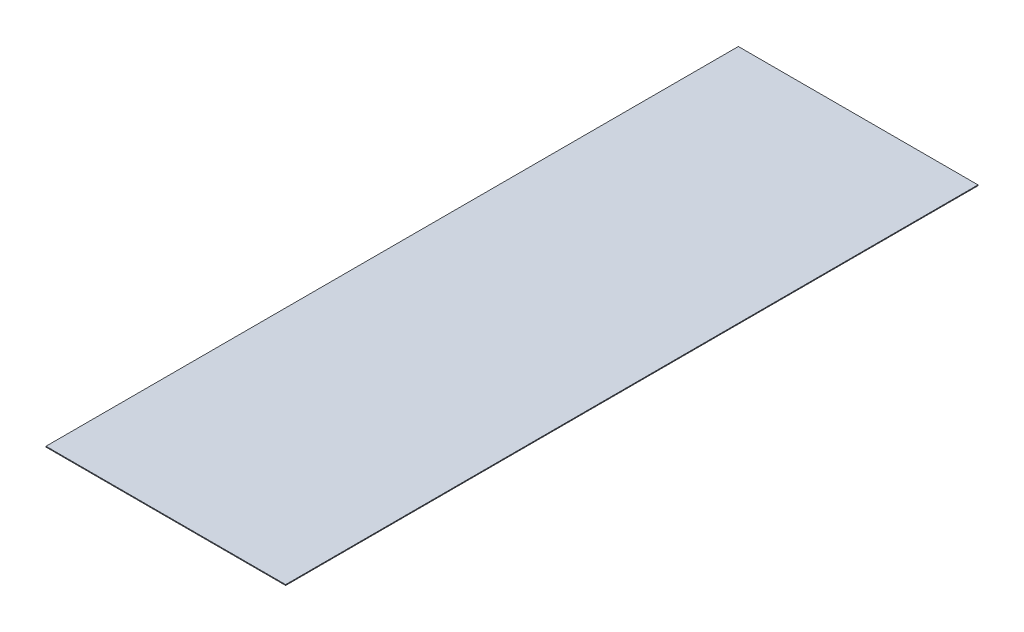
SolidWorks part; units mm, degrees
material "AISI 1018 mild/low carbon Stel"
ref_plane "Front Plane" through (0, 0, 0) normal (0, 0, 1) x (1, 0, 0)
ref_plane "Top Plane" through (0, 0, 0) normal (0, 1, 0) x (1, 0, 0)
ref_plane "Right Plane" through (0, 0, 0) normal (1, 0, 0) x (0, 0, -1)
sketch3d "Suspension Geometry"
  line L0 (0, 0, 150) -> (0, 0, -1405) construction
  line L1 (-213.81, 145.8, 150) -> (213.81, 145.8, 150)
  line L2 (213.81, 145.8, 150) -> (247.07, 302.3, 150)
  line L3 (0, 145.8, 150) -> (0, 0, 150) construction
  line L4 (-247.07, 302.3, 150) -> (247.07, 302.3, 150)
  line L5 (-247.07, 302.3, 150) -> (-213.81, 145.8, 150)
  line L6 (0, 0, -1405) -> (0, 140, -1405) construction
  line L7 (-233.58, 140, -1405) -> (233.58, 140, -1405)
  line L8 (-282.5, 300, -1405) -> (282.5, 300, -1405)
  line L9 (-282.5, 300, -1405) -> (-233.58, 140, -1405)
  line L10 (282.5, 300, -1405) -> (233.58, 140, -1405)
  point P7 (0, 145.8, 150)
  point P12 (0, 140, -1405)
  point P13 (0, 302.3, 150)
  point P17 (0, 300, -1405)
  dimension "D1" = 150
  dimension "D2" = 494.14
  dimension "D3" = 427.62
  dimension "D4" = 145.8
  dimension "D5" = 156.5
  dimension "D6" = 1555
  dimension "D7" = 140
  dimension "D8" = 467.16
  dimension "D9" = 565
  dimension "D10" = 160
sketch3d "Suspension Box"
  line L0 (-282.5, 300, -1405) -> (-282.5, 300, -1145)
  line L1 (-233.58, 140, -1405) -> (-233.58, 140, -1145)
  line L2 (282.5, 300, -1405) -> (282.5, 300, -1145)
  line L3 (233.58, 140, -1405) -> (233.58, 140, -1145)
  line L4 (-282.5, 300, -1145) -> (282.5, 300, -1145) construction
  line L5 (-282.5, 300, -1145) -> (-233.58, 140, -1145) construction
  line L6 (-233.58, 140, -1405) -> (233.58, 140, -1405) construction
  line L7 (282.5, 300, -1145) -> (233.58, 140, -1145) construction
  line L16 (-213.81, 145.8, 0) -> (-213.81, 145.8, 300)
  line L19 (-247.07, 302.3, 0) -> (-247.07, 302.3, 300)
  line L22 (247.07, 302.3, 0) -> (247.07, 302.3, 300)
  line L26 (213.81, 145.8, 0) -> (213.81, 145.8, 300)
  line L28 (-247.07, 302.3, 0) -> (-213.81, 145.8, 0)
  line L29 (247.07, 302.3, 0) -> (213.81, 145.8, 0)
  line L30 (247.07, 302.3, 300) -> (213.81, 145.8, 300)
  line L31 (-247.07, 302.3, 300) -> (-213.81, 145.8, 300)
  point P6 (213.81, 145.8, 150)
  point P8 (-233.58, 140, -1405)
  point P12 (247.07, 302.3, 150)
  point P15 (-282.5, 300, -1405)
  point P16 (-247.07, 302.3, 150)
  point P18 (-213.81, 145.8, 150)
  point P19 (282.5, 300, -1405)
  point P24 (233.58, 140, -1405)
  point P32 (-213.81, 145.8, 150)
  point P35 (-247.07, 302.3, 150)
  point P38 (213.81, 145.8, 150)
  point P40 (247.07, 302.3, 150)
  dimension "D1" = 260
  dimension "D2" = 300
sketch "Percy" plane through (0, 0, 0) normal (1, 0, 0) x (0, 0, -1)
  line L0 (670, 853.9654) -> (670, 573.9654)
  line L1 (670, 573.9654) -> (323.5177, 227.4831)
  line L2 (770, 1191.5162) -> (770, 65) construction
  line L3 (670, 573.9654) -> (670, 368.4293) construction
  line L4 (770, 65) -> (0, 145.8) construction
  line L5 (-52.8264, 166.4257) -> (360.5084, 123.0524) construction
  line L6 (870, 632.544) -> (360.5084, 123.0524)
  line L7 (870, 1120.8087) -> (870, 632.544)
  line L8 (0, 635) -> (770, 1191.5162) construction
  line L9 (323.5177, 227.4831) -> (-582.4403, 355.8)
  line L10 (-150, 65) -> (1405, 65) construction
  line L11 (-150, 0) -> (1405, 0) construction
  line L12 (-0.6994, 554.2948) -> (769.3006, 1110.8109) construction
  circle A0 centre (670, 853.9654) radius 150
  circle A1 centre (670, 573.9654) radius 100
  circle A2 centre (323.5177, 227.4831) radius 100
  point P13 (-875, 145.8)
  point P24 (0, 635)
  point P32 (770, 330)
  dimension "D1" = 200
  dimension "D2" = 300
  dimension "D3" = 280
  dimension "D4" = 490
  dimension "D5" = 45
  dimension "D6" = 15
  dimension "D7" = 770
  dimension "D8" = 200
  dimension "D9" = 875
  dimension "D10" = 915
  dimension "D11" = 210
  dimension "D12" = 65
  dimension "D13" = 570
  dimension "D14" = 65
  dimension "D15" = 265
ref_plane "FH Plane" through (0, 0, 0) normal (0, 0, -1) x (-1, 0, 0)
ref_plane "MH Plane" through (0, 0, -770) normal (0, 0, -1) x (-1, 0, 0)
ref_plane "RBH Plane" through (0, 0, -1405) normal (0, 0, -1) x (-1, 0, 0)
sketch "Sketch2" plane through (0, 0, -770) normal (0, 0, -1) x (-1, 0, 0)
  line L0 (340, 330) -> (-340, 330)
  point P4 (0, 330)
  dimension "D1" = 680
sketch3d "Roll Hoop"
  line L0 (-290, 65, -770) -> (290, 65, -770)
  line L1 (-213.81, 145.8, 0) -> (213.81, 145.8, 0)
  line L2 (-213.81, 145.8, 0) -> (-247.07, 302.3, 0)
  line L4 (-290, 65, -770) -> (-338.2032, 306.5, -770)
  line L6 (290, 65, -770) -> (338.2032, 306.5, -770)
  line L8 (213.81, 145.8, 0) -> (247.07, 302.3, 0)
  line L9 (-249.2546, 535, 0) -> (-249.2546, 323.0881, 0)
  line L10 (249.2546, 535, 0) -> (249.2546, 323.0881, 0)
  line L11 (336.1267, 353.2481, -770) -> (115.1326, 1105.3463, -770)
  line L12 (-115.1326, 1105.3463, -770) -> (-336.1267, 353.2481, -770)
  line L13 (-149.2546, 635, 0) -> (149.2546, 635, 0)
  arc A2 (-338.2032, 306.5, -770) -> (-336.1267, 353.2481, -770) centre (-242.2267, 325.6569, -770) ccw
  arc A5 (249.2546, 535, 0) -> (149.2546, 635, 0) centre (149.2546, 535, 0) ccw
  arc A6 (-249.2546, 535, 0) -> (-149.2546, 635, 0) centre (-149.2546, 535, 0) ccw
  arc A7 (247.07, 302.3, 0) -> (249.2546, 323.0881, 0) centre (149.2546, 323.0881, 0) ccw
  arc A8 (-247.07, 302.3, 0) -> (-249.2546, 323.0881, 0) centre (-149.2546, 323.0881, 0) ccw
  arc A9 (115.1326, 1105.3463, -770) -> (-115.1326, 1105.3463, -770) centre (0, 1071.5162, -770) ccw
  arc A10 (336.1267, 353.2481, -770) -> (338.2032, 306.5, -770) centre (242.2267, 325.6569, -770) ccw
  point P8 (0, 65, -770)
  point P13 (242.2267, 325.6569, -867.8698)
  point P23 (0, 1071.5162, -650)
  point P24 (-242.2267, 325.6569, -867.8698)
  point P26 (-340, 330, -770)
  point P27 (0, 1191.5162, -770)
  point P30 (0, 145.8, 0)
  point P35 (-340, 330, -770)
  point P39 (249.2546, 635, 0)
  point P40 (149.2546, 535, 100)
  point P46 (-249.2546, 635, 0)
  point P47 (-149.2546, 535, -100)
  point P48 (0, 635, 0)
  point P50 (249.2546, 312.5793, 0)
  point P51 (149.2546, 323.0881, 100)
  point P54 (-149.2546, 323.0881, -100)
  point P56 (242.5, 635, 0)
  point P59 (-242.5, 635, 0)
  dimension "D2" = 120
  dimension "D5" = 100
  dimension "D1" = 580
  dimension "D4" = 241.5
sketch3d "FBH"
  line L0 (-212.5, 145.8, 875) -> (212.5, 145.8, 875)
  line L1 (212.5, 145.8, 875) -> (212.5, 520.8, 875)
  line L2 (212.5, 520.8, 875) -> (-212.5, 520.8, 875)
  line L3 (-212.5, 520.8, 875) -> (-212.5, 145.8, 875)
  line L4 (-212.5, 520.8, 875) -> (212.5, 145.8, 875)
  line L5 (-210.6176, 65, -1405) -> (210.6176, 65, -1405)
  line L6 (208.7935, 444.65, -1405) -> (282.5, 300, -1405)
  line L7 (-282.5, 300, -1405) -> (-210.6176, 65, -1405)
  line L8 (-208.7935, 444.65, -1405) -> (208.7935, 444.65, -1405)
  line L9 (-282.5, 300, -1405) -> (282.5, 300, -1405) construction
  line L10 (0, 444.65, -1405) -> (0, 414.65, -1405) construction
  line L11 (0, 414.65, -1405) -> (224.08, 414.65, -1405) construction
  line L12 (-208.7935, 444.65, -1405) -> (-282.5, 300, -1405)
  line L13 (210.6176, 65, -1405) -> (282.5, 300, -1405)
  line L14 (0, 414.65, -1405) -> (-224.08, 414.65, -1405) construction
  line L18 (282.5, 300, -1405) -> (233.5606, 140.0059, -1405) construction
  line L19 (-282.5, 300, -1405) -> (-233.5606, 140.0059, -1405) construction
  line L20 (0, 65, 150) -> (0, 65, -1405) construction
  point P4 (0, 145.8, 875)
  point P17 (0, 444.65, -1405)
  point P28 (0, 65, -1405)
  dimension "D1" = 425
  dimension "D2" = 375
  dimension "D4" = 144.65
  dimension "D5" = 224.08
  dimension "D6" = 30
sketch3d "Members"
  line L0 (212.5, 520.8, 875) -> (229.2546, 595, 0)
  line L1 (-212.5, 520.8, 875) -> (-229.2546, 595, 0)
  line L2 (247.07, 302.3, 300) -> (212.5, 520.8, 875)
  line L3 (213.81, 145.8, 300) -> (212.5, 145.8, 875)
  line L4 (-213.81, 145.8, 300) -> (-212.5, 145.8, 875)
  line L5 (-212.5, 145.8, 875) -> (-247.07, 302.3, 300)
  line L6 (-247.07, 302.3, 300) -> (-212.5, 520.8, 875)
  line L7 (-149.2546, 635, 0) -> (149.2546, 635, 0) construction
  line L8 (-247.07, 302.3, 300) -> (-226.3682, 582.2173, 150.739)
  line L9 (210.6176, 65, -1405) -> (282.5, 300, -1405) construction
  line L10 (-282.5, 300, -1405) -> (-210.6176, 65, -1405) construction
  line L11 (248.9273, 315.0042, 0) -> (340, 330, -770)
  line L12 (340, 330, -770) -> (282.5, 300, -1145)
  line L14 (-340, 330, -770) -> (-248.9273, 315.0042, 0)
  line L15 (229.2546, 595, 0) -> (290.0297, 321.772, -347.5123)
  line L16 (340, 330, -770) -> (233.58, 140, -1145)
  line L17 (290.0297, 321.772, -347.5123) -> (213.81, 145.8, 0)
  line L18 (-213.81, 145.8, 0) -> (-290, 65, -770)
  line L19 (290, 65, -770) -> (213.81, 145.8, 0)
  line L20 (-226.3682, 582.2173, 150.739) -> (226.3682, 582.2173, 150.739)
  line L21 (290.0297, 321.772, -347.5123) -> (290, 65, -770)
  line L22 (-229.2546, 595, 0) -> (-290.0297, 321.772, -347.5123)
  line L23 (-340, 330, -770) -> (-282.5, 300, -1145)
  line L25 (290, 65, -770) -> (233.58, 140, -1145)
  line L26 (-290.0297, 321.772, -347.5123) -> (-213.81, 145.8, 0)
  line L27 (-290.0297, 321.772, -347.5123) -> (-290, 65, -770)
  line L28 (226.3682, 582.2173, 150.739) -> (248.9273, 315.0042, 0)
  line L29 (-244.5225, 665, -770) -> (244.5225, 665, -770)
  line L30 (290, 65, -770) -> (210.6176, 65, -1145)
  line L31 (247.07, 302.3, 300) -> (226.3682, 582.2173, 150.739)
  line L32 (-290, 65, -770) -> (290, 65, -770) construction
  line L33 (-246.7006, 110.9193, -332.4027) -> (246.7006, 110.9193, -332.4027)
  line L34 (-223.6508, 135.3638, -99.4539) -> (223.6508, 135.3638, -99.4539)
  line L35 (-213.81, 145.8, 0) -> (213.81, 145.8, 0) construction
  line L36 (247.07, 302.3, 300) -> (212.5, 145.8, 875)
  line L37 (210.6176, 65, -1145) -> (210.6176, 65, -1405)
  line L38 (-226.3682, 582.2173, 150.739) -> (-248.9273, 315.0042, 0)
  line L42 (-290, 65, -770) -> (-210.6176, 65, -1145)
  line L43 (133.8883, 1041.5162, -770) -> (282.5, 300, -1405)
  line L47 (-282.5, 300, -1145) -> (-210.6176, 65, -1145)
  line L51 (210.6176, 65, -1145) -> (282.5, 300, -1145)
  line L52 (-133.8883, 1041.5162, -770) -> (-282.5, 300, -1405)
  line L53 (-133.8883, 1041.5162, -770) -> (133.8883, 1041.5162, -770) construction
  line L54 (-115.1326, 1105.3463, -770) -> (-336.1267, 353.2481, -770) construction
  line L55 (-213.81, 145.8, 300) -> (213.81, 145.8, 300)
  line L57 (336.1267, 353.2481, -770) -> (115.1326, 1105.3463, -770) construction
  line L58 (-210.6176, 65, -1405) -> (-210.6176, 65, -1145)
  line L59 (-282.5, 300, -1405) -> (-282.5, 300, -1402.3763)
  line L60 (282.5, 300, -1405) -> (233.58, 140, -1145)
  line L61 (-210.6176, 65, -1145) -> (210.6176, 65, -1145)
  line L62 (233.58, 140, -1405) -> (210.6176, 65, -1145)
  line L63 (-290, 65, -770) -> (-233.58, 140, -1145)
  line L64 (-233.58, 140, -1145) -> (-340, 330, -770)
  line L65 (-233.58, 140, -1405) -> (-210.6176, 65, -1145)
  line L66 (0, 65, 150) -> (0, 65, -1405) construction
  line L67 (-282.5, 300, -1405) -> (-233.58, 140, -1145)
  arc A0 (247.07, 302.3, 0) -> (249.2546, 323.0881, 0) centre (149.2546, 323.0881, 0) ccw construction
  arc A1 (-247.07, 302.3, 0) -> (-249.2546, 323.0881, 0) centre (-149.2546, 323.0881, 0) ccw construction
  arc A4 (249.2546, 535, 0) -> (149.2546, 635, 0) centre (149.2546, 535, 0) ccw construction
  arc A8 (-249.2546, 535, 0) -> (-149.2546, 635, 0) centre (-149.2546, 535, 0) ccw construction
  point P6 (149.2546, 535, 100)
  point P25 (-149.2546, 535, -100)
  point P51 (149.2546, 323.0881, 100)
  point P91 (0, 65, -1145)
  point P93 (-149.2546, 323.0881, -100)
  dimension "D7" = 150
  dimension "D1" = 40
  dimension "D2" = 172.81
  dimension "D8" = 151.28
  dimension "D3" = 600
  dimension "D4" = 350
  dimension "D5" = 440
  dimension "D6" = 100
other "Square tube 25.4X25.4X1.6(1)"
ref_plane "Plane1" [suppressed] through (212.5, 520.8, 875) normal (-1, 0, 0) x (0, 0, 1)
sketch "Sketch1" [suppressed] plane through (212.5, 520.8, 875) normal (-1, 0, 0) x (0, 0, 1)
  line L0 (-11.1, 11.1) -> (11.1, 11.1)
  line L1 (-12.7, 12.7) -> (12.7, 12.7)
  line L2 (-12.7, 12.7) -> (-12.7, -12.7)
  line L3 (-12.7, -12.7) -> (12.7, -12.7)
  line L4 (12.7, 12.7) -> (12.7, -12.7)
  line L5 (-12.7, 12.7) -> (12.7, -12.7) construction
  line L6 (-12.7, -12.7) -> (12.7, 12.7) construction
  line L7 (11.1, 11.1) -> (11.1, -11.1)
  line L8 (-11.1, -11.1) -> (11.1, -11.1)
  line L9 (-11.1, 11.1) -> (-11.1, -11.1)
  point P0 (0, 0)
  point P10 (0, 0)
  dimension "D1" = 25.4
  dimension "D2" = 25.4
  dimension "D3" = 1.6
other "Pipe 25.4X1.6(1)"
ref_plane "Plane2" [suppressed] through (213.81, 145.8, 300) normal (-0.0023, 0, 1) x (1, 0, 0.0023)
sketch "Sketch11" [suppressed] plane through (213.81, 145.8, 300) normal (-0.0023, 0, 1) x (1, 0, 0.0023)
  circle A0 centre (0, 0) radius 12.7
  circle A1 centre (0, 0) radius 11.1
  point P5 (0, 0)
  dimension "D1" = 25.4
  dimension "D2" = 1.6
other "Trim/Extend1" [suppressed]
other "Pipe 25.4X2.5(4)"
ref_plane "Plane9" [suppressed] through (-213.81, 145.8, 0) normal (1, 0, 0) x (0, 0, -1)
sketch "Sketch19" [suppressed] plane through (-213.81, 145.8, 0) normal (1, 0, 0) x (0, 0, -1)
  circle A0 centre (0, 0) radius 12.7
  circle A1 centre (0, 0) radius 10.2
  point P5 (0, 0)
  dimension "D1" = 25.4
  dimension "D2" = 2.5
other "Trim/Extend8" [suppressed]
other "Trim/Extend9" [suppressed]
other "Pipe 25.4X2.5(1)"
ref_plane "Plane3" [suppressed] through (247.07, 302.3, 0) normal (-0.2079, -0.9782, 0) x (0.9568, -0.2033, 0.2079)
sketch "Sketch12" [suppressed] plane through (247.07, 302.3, 0) normal (-0.2079, -0.9782, 0) x (0.9568, -0.2033, 0.2079)
  circle A0 centre (0, 0) radius 12.7
  circle A1 centre (0, 0) radius 10.2
  point P5 (0, 0)
  dimension "D1" = 25.4
  dimension "D2" = 2.5
other "Trim/Extend2" [suppressed]
other "Pipe 25.4X2.5(2)"
ref_plane "Plane4" [suppressed] through (290, 65, -770) normal (0.1957, 0.9807, 0) x (0.9617, -0.192, -0.1957)
sketch "Sketch13" [suppressed] plane through (290, 65, -770) normal (0.1957, 0.9807, 0) x (0.9617, -0.192, -0.1957)
  circle A0 centre (0, 0) radius 12.7
  circle A1 centre (0, 0) radius 10.2
  point P5 (0, 0)
  dimension "D1" = 25.4
  dimension "D2" = 2.5
other "Trim/Extend3" [suppressed]
other "Pipe 25.4X2.5(3)"
ref_plane "Plane6" [suppressed] through (-244.5225, 665, -770) normal (1, 0, 0) x (0, 0, -1)
sketch "Sketch16" [suppressed] plane through (-244.5225, 665, -770) normal (1, 0, 0) x (0, 0, -1)
  circle A0 centre (0, 0) radius 12.7
  circle A1 centre (0, 0) radius 10.2
  point P5 (0, 0)
  dimension "D1" = 25.4
  dimension "D2" = 2.5
other "Trim/Extend4" [suppressed]
other "Pipe 25.4X1.6(3)"
ref_plane "Plane7" [suppressed] through (-340, 330, -770) normal (1, 0, 0) x (0, -1, 0)
sketch "Sketch17" [suppressed] plane through (-340, 330, -770) normal (1, 0, 0) x (0, -1, 0)
  circle A0 centre (0, 0) radius 12.7
  circle A1 centre (0, 0) radius 11.1
  point P5 (0, 0)
  dimension "D1" = 25.4
  dimension "D2" = 1.6
other "Trim/Extend5" [suppressed]
other "Trim/Extend6" [suppressed]
other "Trim/Extend7" [suppressed]
other "Pipe 25.4X1.6(4)"
ref_plane "Plane10" [suppressed] through (-210.6176, 65, -1405) normal (1, 0, 0) x (0, 0, -1)
sketch "Sketch110" [suppressed] plane through (-210.6176, 65, -1405) normal (1, 0, 0) x (0, 0, -1)
  circle A0 centre (0, 0) radius 12.7
  circle A1 centre (0, 0) radius 11.1
  point P5 (0, 0)
  dimension "D1" = 25.4
  dimension "D2" = 1.6
other "Trim/Extend10" [suppressed]
other "Pipe 25.4X1.6(5)"
ref_plane "Plane11" [suppressed] through (212.5, 520.8, 875) normal (0.0191, 0.0845, -0.9962) x (0.9032, -0.4289, -0.0191)
sketch "Sketch111" [suppressed] plane through (212.5, 520.8, 875) normal (0.0191, 0.0845, -0.9962) x (0.9032, -0.4289, -0.0191)
  circle A0 centre (0, 0) radius 12.7
  circle A1 centre (0, 0) radius 11.1
  point P5 (0, 0)
  dimension "D1" = 25.4
  dimension "D2" = 1.6
other "Trim/Extend45" [suppressed]
other "Trim/Extend47" [suppressed]
other "Pipe 25.4X1.2(73)"
ref_plane "Plane30" [suppressed] through (247.07, 302.3, 300) normal (-0.0579, -0.2622, 0.9633) x (0.9983, -0.0077, 0.0579)
sketch "Sketch138" [suppressed] plane through (247.07, 302.3, 300) normal (-0.0579, -0.2622, 0.9633) x (0.9983, -0.0077, 0.0579)
  circle A0 centre (0, 0) radius 12.7
  circle A1 centre (0, 0) radius 11.5
  point P5 (0, 0)
  point P6 (0, 0)
  dimension "D1" = 25.4
  dimension "D2" = 1.2
other "Trim/Extend49" [suppressed]
other "Trim/Extend50" [suppressed]
other "Pipe 25.4X1.2(74)"
ref_plane "Plane31" [suppressed] through (247.07, 302.3, 300) normal (-0.2079, -0.9782, 0) x (0.9568, -0.2033, 0.2079)
sketch "Sketch139" [suppressed] plane through (247.07, 302.3, 300) normal (-0.2079, -0.9782, 0) x (0.9568, -0.2033, 0.2079)
  circle A0 centre (0, 0) radius 12.7
  circle A1 centre (0, 0) radius 11.5
  point P5 (0, 0)
  dimension "D1" = 25.4
  dimension "D2" = 1.2
other "Trim/Extend52" [suppressed]
other "Pipe 25.4X1.2(75)"
ref_plane "Plane32" [suppressed] through (247.07, 302.3, 300) normal (-0.0561, 0.3547, 0.9333) x (0.9984, 0.0103, 0.0561)
sketch "Sketch140" [suppressed] plane through (247.07, 302.3, 300) normal (-0.0561, 0.3547, 0.9333) x (0.9984, 0.0103, 0.0561)
  circle A0 centre (0, 0) radius 12.7
  circle A1 centre (0, 0) radius 11.5
  point P5 (0, 0)
  dimension "D1" = 25.4
  dimension "D2" = 1.2
other "Trim/Extend54" [suppressed]
other "Pipe 25.4X1.2(3)"
ref_plane "Plane15" [suppressed] through (247.07, 302.3, 300) normal (-0.0651, 0.8805, -0.4695) x (0.992, 0.1081, 0.0651)
sketch "Sketch115" [suppressed] plane through (247.07, 302.3, 300) normal (-0.0651, 0.8805, -0.4695) x (0.992, 0.1081, 0.0651)
  circle A0 centre (0, 0) radius 12.7
  circle A1 centre (0, 0) radius 11.5
  point P5 (0, 0)
  dimension "D1" = 25.4
  dimension "D2" = 1.2
other "Trim/Extend22" [suppressed]
other "Pipe 25.4X1.2(4)"
ref_plane "Plane16" [suppressed] through (-226.3682, 582.2173, 150.739) normal (-0.0733, -0.8686, -0.49) x (0.9895, -0.1249, 0.0733)
sketch "Sketch116" [suppressed] plane through (-226.3682, 582.2173, 150.739) normal (-0.0733, -0.8686, -0.49) x (0.9895, -0.1249, 0.0733)
  circle A0 centre (0, 0) radius 12.7
  circle A1 centre (0, 0) radius 11.5
  point P5 (0, 0)
  dimension "D1" = 25.4
  dimension "D2" = 1.2
other "Trim/Extend23" [suppressed]
other "Trim/Extend55" [suppressed]
other "Pipe 25.4X1.2(5)"
ref_plane "Plane17" [suppressed] through (-226.3682, 582.2173, 150.739) normal (1, 0, 0) x (0, 0, -1)
sketch "Sketch117" [suppressed] plane through (-226.3682, 582.2173, 150.739) normal (1, 0, 0) x (0, 0, -1)
  circle A0 centre (0, 0) radius 12.7
  circle A1 centre (0, 0) radius 11.5
  point P5 (0, 0)
  dimension "D1" = 25.4
  dimension "D2" = 1.2
other "Trim/Extend25" [suppressed]
other "Pipe 25.4X1.6(23)"
ref_plane "Plane18" [suppressed] through (-340, 330, -770) normal (0.1174, -0.0193, 0.9929) x (0.9931, 0.0011, -0.1174)
sketch "Sketch119" [suppressed] plane through (-340, 330, -770) normal (0.1174, -0.0193, 0.9929) x (0.9931, 0.0011, -0.1174)
  circle A0 centre (0, 0) radius 12.7
  circle A1 centre (0, 0) radius 11.1
  point P5 (0, 0)
  dimension "D1" = 25.4
  dimension "D2" = 1.6
other "Trim/Extend26" [suppressed]
other "Trim/Extend56" [suppressed]
other "Pipe 25.4X1.2(16)"
ref_plane "Plane20" [suppressed] through (-229.2546, 595, 0) normal (-0.1362, -0.6123, -0.7788) x (0.9161, -0.377, 0.1362)
sketch "Sketch121" [suppressed] plane through (-229.2546, 595, 0) normal (-0.1362, -0.6123, -0.7788) x (0.9161, -0.377, 0.1362)
  circle A0 centre (0, 0) radius 12.7
  circle A1 centre (0, 0) radius 11.5
  point P5 (0, 0)
  dimension "D1" = 25.4
  dimension "D2" = 1.2
other "Trim/Extend29" [suppressed]
other "Trim/Extend57" [suppressed]
other "Pipe 25.4X1.6(24)"
ref_plane "Plane19" [suppressed] through (290.0297, 321.772, -347.5123) normal (-0.192, -0.4434, 0.8755) x (0.9803, -0.0454, 0.192)
sketch "Sketch120" [suppressed] plane through (290.0297, 321.772, -347.5123) normal (-0.192, -0.4434, 0.8755) x (0.9803, -0.0454, 0.192)
  circle A0 centre (0, 0) radius 12.7
  circle A1 centre (0, 0) radius 11.1
  point P5 (0, 0)
  dimension "D1" = 25.4
  dimension "D2" = 1.6
other "Trim/Extend58" [suppressed]
other "Pipe 25.4X1.6(228)"
ref_plane "Plane33" [suppressed] through (290.0297, 321.772, -347.5123) normal (-0.0001, -0.5194, -0.8546) x (1, -0.0002, 0.0001)
sketch "Sketch141" [suppressed] plane through (290.0297, 321.772, -347.5123) normal (-0.0001, -0.5194, -0.8546) x (1, -0.0002, 0.0001)
  circle A0 centre (0, 0) radius 12.7
  circle A1 centre (0, 0) radius 11.1
  point P5 (0, 0)
  dimension "D1" = 25.4
  dimension "D2" = 1.6
other "Trim/Extend60" [suppressed]
other "Pipe 25.4X1.6(25)"
ref_plane "Plane21" [suppressed] through (-340, 330, -770) normal (0.1511, -0.0788, -0.9854) x (-0.5606, 0.8142, -0.1511)
sketch "Sketch122" [suppressed] plane through (-340, 330, -770) normal (0.1511, -0.0788, -0.9854) x (-0.5606, 0.8142, -0.1511)
  circle A0 centre (0, 0) radius 12.7
  circle A1 centre (0, 0) radius 11.1
  point P5 (0, 0)
  dimension "D1" = 25.4
  dimension "D2" = 1.6
other "Trim/Extend30" [suppressed]
other "Pipe 25.4X1.6(26)"
ref_plane "Plane22" [suppressed] through (-133.8883, 1041.5162, -770) normal (-0.1505, -0.7509, -0.643) x (0.9366, -0.3166, 0.1505)
sketch "Sketch123" [suppressed] plane through (-133.8883, 1041.5162, -770) normal (-0.1505, -0.7509, -0.643) x (0.9366, -0.3166, 0.1505)
  circle A0 centre (0, 0) radius 12.7
  circle A1 centre (0, 0) radius 11.1
  point P5 (0, 0)
  dimension "D1" = 25.4
  dimension "D2" = 1.6
other "Trim/Extend31" [suppressed]
other "Pipe 25.4X1.6(27)"
ref_plane "Plane23" [suppressed] through (-282.5, 300, -1145) normal (0.2925, -0.9563, 0) x (0.9144, 0.2797, -0.2925)
sketch "Sketch124" [suppressed] plane through (-282.5, 300, -1145) normal (0.2925, -0.9563, 0) x (0.9144, 0.2797, -0.2925)
  circle A0 centre (0, 0) radius 12.7
  circle A1 centre (0, 0) radius 11.1
  point P5 (0, 0)
  dimension "D1" = 25.4
  dimension "D2" = 1.6
other "Trim/Extend32" [suppressed]
other "Pipe 25.4X1.6(28)"
ref_plane "Plane24" [suppressed] through (340, 330, -770) normal (-0.2454, -0.4381, -0.8648) x (0.5547, -0.795, 0.2454)
sketch "Sketch125" [suppressed] plane through (340, 330, -770) normal (-0.2454, -0.4381, -0.8648) x (0.5547, -0.795, 0.2454)
  circle A0 centre (0, 0) radius 12.7
  circle A1 centre (0, 0) radius 11.1
  point P5 (0, 0)
  dimension "D1" = 25.4
  dimension "D2" = 1.6
other "Trim/Extend33" [suppressed]
other "Pipe 25.4X1.6(30)"
ref_plane "Plane25" [suppressed] through (290, 65, -770) normal (-0.146, 0.194, -0.9701) x (0.288, 0.9464, 0.146)
sketch "Sketch126" [suppressed] plane through (290, 65, -770) normal (-0.146, 0.194, -0.9701) x (0.288, 0.9464, 0.146)
  circle A0 centre (0, 0) radius 12.7
  circle A1 centre (0, 0) radius 11.1
  point P5 (0, 0)
  dimension "D1" = 25.4
  dimension "D2" = 1.6
other "Trim/Extend35" [suppressed]
other "Pipe 25.4X1.6(31)"
ref_plane "Plane26" [suppressed] through (233.58, 140, -1405) normal (0, 0, 1) x (1, 0, 0)
sketch "Sketch127" [suppressed] plane through (233.58, 140, -1405) normal (0, 0, 1) x (1, 0, 0)
  circle A0 centre (0, 0) radius 12.7
  circle A1 centre (0, 0) radius 11.1
  point P5 (0, 0)
  dimension "D1" = 25.4
  dimension "D2" = 1.6
other "Trim/Extend37" [suppressed]
other "Pipe 25.4X1.6(131)"
ref_plane "Plane27" [suppressed] through (-282.5, 300, -1405) normal (0.1582, -0.5175, 0.8409) x (0.9864, 0.0445, -0.1582)
sketch "Sketch135" [suppressed] plane through (-282.5, 300, -1405) normal (0.1582, -0.5175, 0.8409) x (0.9864, 0.0445, -0.1582)
  circle A0 centre (0, 0) radius 12.7
  circle A1 centre (0, 0) radius 11.1
  point P5 (0, 0)
  dimension "D1" = 25.4
  dimension "D2" = 1.6
other "Trim/Extend38" [suppressed]
other "Pipe 12X3.5(1)"
ref_plane "Plane28" [suppressed] through (-213.81, 145.8, 300) normal (1, 0, 0) x (0, 0, -1)
sketch "Sketch130" [suppressed] plane through (-213.81, 145.8, 300) normal (1, 0, 0) x (0, 0, -1)
  circle A0 centre (0, 0) radius 6
  circle A1 centre (0, 0) radius 2.5
  point P5 (0, 0)
  dimension "D1" = 12
  dimension "D2" = 3.5
other "Trim/Extend39" [suppressed]
other "Pipe 12X3.5(2)"
ref_plane "Plane29" [suppressed] through (233.58, 140, -1405) normal (-0.0846, -0.2762, 0.9574) x (0.9963, -0.0119, 0.0846)
sketch "Sketch131" [suppressed] plane through (233.58, 140, -1405) normal (-0.0846, -0.2762, 0.9574) x (0.9963, -0.0119, 0.0846)
  circle A0 centre (0, 0) radius 6
  circle A1 centre (0, 0) radius 2.5
  point P5 (0, 0)
  dimension "D1" = 12
  dimension "D2" = 3.5
other "Trim/Extend40" [suppressed]
combine bodies "Combine12" [suppressed] operation type add bodies to combine 284 283 128 282 285 467 465 133 459 477 478 460 474 132 473 275 207 206 470 145 140 469 162 147 480 215 479 485 481 482 486 483 484 490 489 144 139 158 157 163
sketch "Sketch142" plane through (0, 0, 0) normal (0, 1, 0) x (1, 0, 0)
  line L1 (450, -1006.1698) -> (-450, -1006.1698)
  line L2 (450, -1006.1698) -> (450, 1593.8302)
  line L3 (450, 1593.8302) -> (-450, 1593.8302)
  line L4 (-450, -1006.1698) -> (-450, 1593.8302)
  dimension "D1" = 2600
  dimension "D2" = 900
  dimension "D3" = 450
extrude "Boss-Extrude1" add sketch "Sketch142" along normal blind 3 separate body
